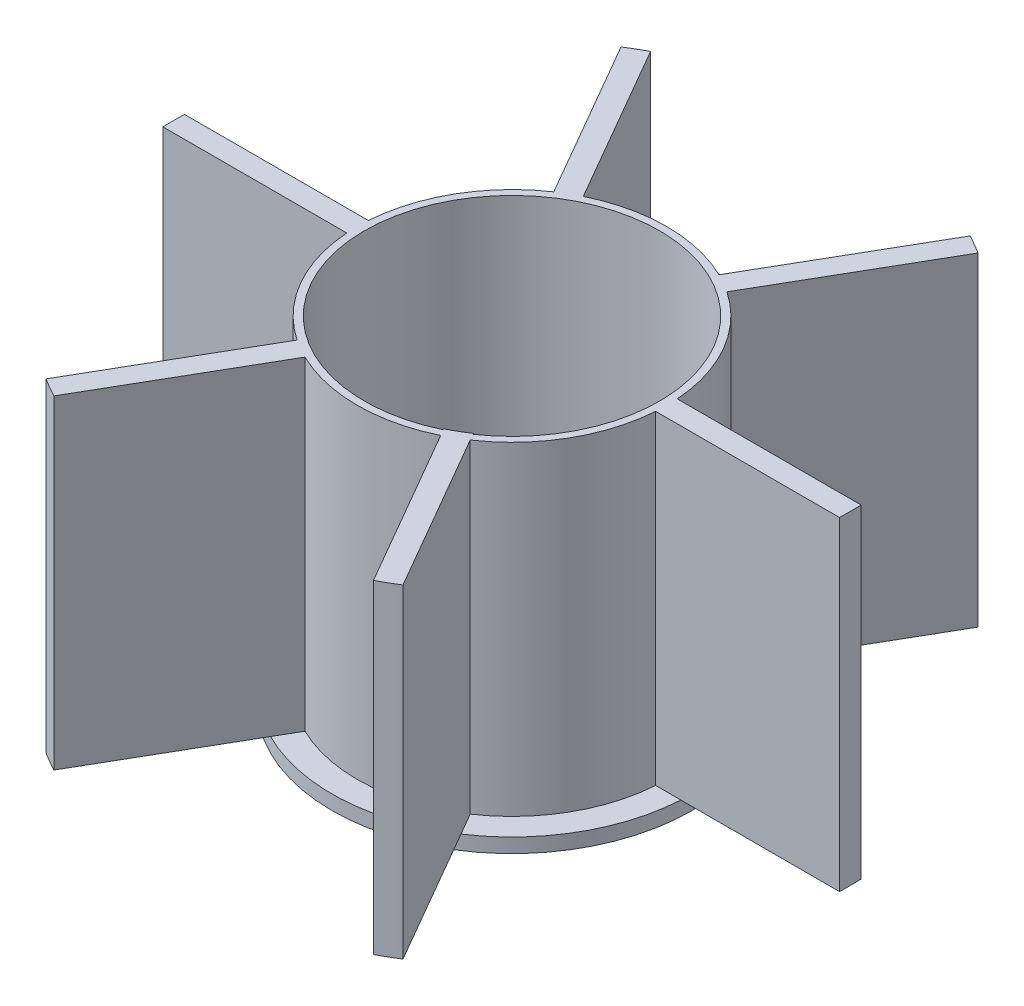
SolidWorks part; units mm, degrees
ref_plane "前视基准面" through (0, 0, 0) normal (0, 0, 1) x (1, 0, 0)
ref_plane "上视基准面" through (0, 0, 0) normal (0, 1, 0) x (1, 0, 0)
ref_plane "右视基准面" through (0, 0, 0) normal (1, 0, 0) x (0, 0, -1)
other "Configuration Table"
sketch "草图1" plane through (0, 0, 0) normal (0, 1, 0) x (1, 0, 0)
  circle A0 centre (0, 0) radius 25
  dimension "D1" = 50
extrude "凸台-拉伸2" add sketch "草图1" along normal blind 2 contours A0
sketch "草图2" plane through (0, 2, 0) normal (0, 1, 0) x (1, 0, 0)
  line L0 (0, 0) -> (47, 0) construction
  line L1 (0, 0) -> (-47, 0) construction
  line L2 (0, 0) -> (23.5, 40.7032) construction
  line L3 (0, 0) -> (-23.5, 40.7032) construction
  line L4 (0, 0) -> (-23.5, -40.7032) construction
  line L5 (0, 0) -> (23.5, -40.7032) construction
  line L6 (46.9761, -1.5) -> (20.445, -1.5)
  line L7 (20.445, 1.5) -> (46.9761, 1.5)
  line L8 (8.8401, -18.3115) -> (22.1895, -41.4333)
  line L9 (24.7874, -39.9334) -> (11.438, -16.8116)
  line L10 (-8.9235, -18.4559) -> (-22.189, -41.4325)
  line L11 (-11.5216, -16.9559) -> (-24.7871, -39.9325)
  line L12 (-20.445, 1.5) -> (-46.9761, 1.5)
  line L13 (-20.445, -1.5) -> (-46.9761, -1.5)
  line L14 (-11.5216, 16.9559) -> (-24.7871, 39.9325)
  line L15 (-8.9235, 18.4559) -> (-22.189, 41.4325)
  line L16 (8.9235, 18.4559) -> (22.189, 41.4325)
  line L17 (11.5216, 16.9559) -> (24.7871, 39.9325)
  circle A0 centre (0, 0) radius 20.5 construction
  circle A1 centre (0, 0) radius 47 construction
  arc A2 (20.445, -1.5) -> (20.445, 1.5) centre (0, 0) ccw
  arc A3 (46.9761, -1.5) -> (46.9761, 1.5) centre (0, 0) ccw
  arc A6 (24.7874, -39.9334) -> (22.1895, -41.4333) centre (0, 0) cw
  arc A7 (11.438, -16.8116) -> (8.8401, -18.3115) centre (0, 0) cw
  arc A8 (-8.9235, -18.4559) -> (-11.5216, -16.9559) centre (0, 0) cw
  arc A9 (-22.189, -41.4325) -> (-24.7871, -39.9325) centre (0, 0) cw
  arc A10 (-20.445, -1.5) -> (-20.445, 1.5) centre (0, 0) cw
  arc A11 (-46.9761, -1.5) -> (-46.9761, 1.5) centre (0, 0) cw
  arc A12 (-11.5216, 16.9559) -> (-8.9235, 18.4559) centre (0, 0) cw
  arc A13 (-24.7871, 39.9325) -> (-22.189, 41.4325) centre (0, 0) cw
  arc A14 (8.9235, 18.4559) -> (11.5216, 16.9559) centre (0, 0) cw
  arc A15 (22.189, 41.4325) -> (24.7871, 39.9325) centre (0, 0) cw
  dimension "D1" = 41
  dimension "D2" = 94
  dimension "D17" = 20.3337
  dimension "D18" = 1.5
  dimension "D3" = 60
  dimension "D4" = 60
  dimension "D5" = 60
  dimension "D6" = 60
  dimension "D7" = 3
  dimension "D8" = 1.5
  dimension "D9" = 0
  dimension "D10" = 1.5
  dimension "D11" = 360
  dimension "D12" = 1.5
  dimension "D13" = 1.4998
  dimension "D14" = 2.9998
  dimension "D15" = 2.9998
  dimension "D16" = 2.9998
  dimension "D19" = 1.5
  dimension "D20" = 1.5
  dimension "D21" = 1.5
  dimension "D22" = 1.5
  dimension "D23" = 1.5
  dimension "D24" = 1.5
  dimension "D25" = 1.5
extrude "凸台-拉伸3" add sketch "草图2" along normal blind 45
sketch "草图3" plane through (0, 2, 0) normal (0, 1, 0) x (1, 0, 0)
  circle A0 centre (0, 0) radius 20.5
  circle A1 centre (0, 0) radius 21.5
  dimension "D1" = 41
  dimension "D2" = 43
extrude "凸台-拉伸4" add sketch "草图3" along normal blind 45
sketch "草图4"
sketch "草图5" plane through (0, 2, 0) normal (0, 1, 0) x (1, 0, 0)
  circle A0 centre (0, 0) radius 21.5
extrude "凸台-拉伸5" add sketch "草图5" along normal blind 16
sketch "草图6" plane through (0, 18, 0) normal (0, 1, 0) x (1, 0, 0)
  line L0 (0, 0) -> (0, 17) construction
  line L1 (0, 0) -> (0, -20) construction
  line L2 (-8.35, 0) -> (8.35, 0) construction
  line L3 (-12.69, 1.95) -> (14.4028, 1.95) construction
  line L4 (-13.6243, -1.95) -> (14.4028, -1.95) construction
  line L5 (2.1, 14.9) -> (2.9, 1.95)
  line L6 (-2.1, 14.9) -> (-2.9, 1.95)
  line L7 (-3.5, -1.95) -> (-2.1, -17.9)
  line L8 (3.5, -1.95) -> (2.1, -17.9)
  line L9 (-8.35, 1.95) -> (-2.9, 1.95)
  line L10 (2.9, 1.95) -> (8.35, 1.95)
  line L11 (-8.35, -1.95) -> (-3.5, -1.95)
  line L12 (3.5, -1.95) -> (8.35, -1.95)
  arc A0 (-2.1, 14.9) -> (2.1, 14.9) centre (0, 14.9) cw
  arc A1 (-2.1, -17.9) -> (2.1, -17.9) centre (0, -17.9) ccw
  arc A2 (8.35, 1.95) -> (8.35, -1.95) centre (8.35, 0) cw
  arc A3 (-8.35, 1.95) -> (-8.35, -1.95) centre (-8.35, 0) ccw
  dimension "D3" = 2.1
  dimension "D9" = 2.1
  dimension "D17" = 1.95
  dimension "D18" = 1.95
  dimension "D1" = 1.95
  dimension "D2" = 1.95
  dimension "D4" = 2.9
  dimension "D5" = 2.9
  dimension "D6" = 17
  dimension "D7" = 2.1
  dimension "D8" = 2.1
  dimension "D10" = 3.5
  dimension "D11" = 3.5
  dimension "D12" = 2.1
  dimension "D13" = 2.1
  dimension "D14" = 20
  dimension "D15" = 16.7
  dimension "D16" = 8.35
extrude "切除-拉伸1" cut sketch "草图6" against normal blind 16 contours L6 L9 A3 L11 L7 A1 L8 L12 A2 L10 L5 A0
